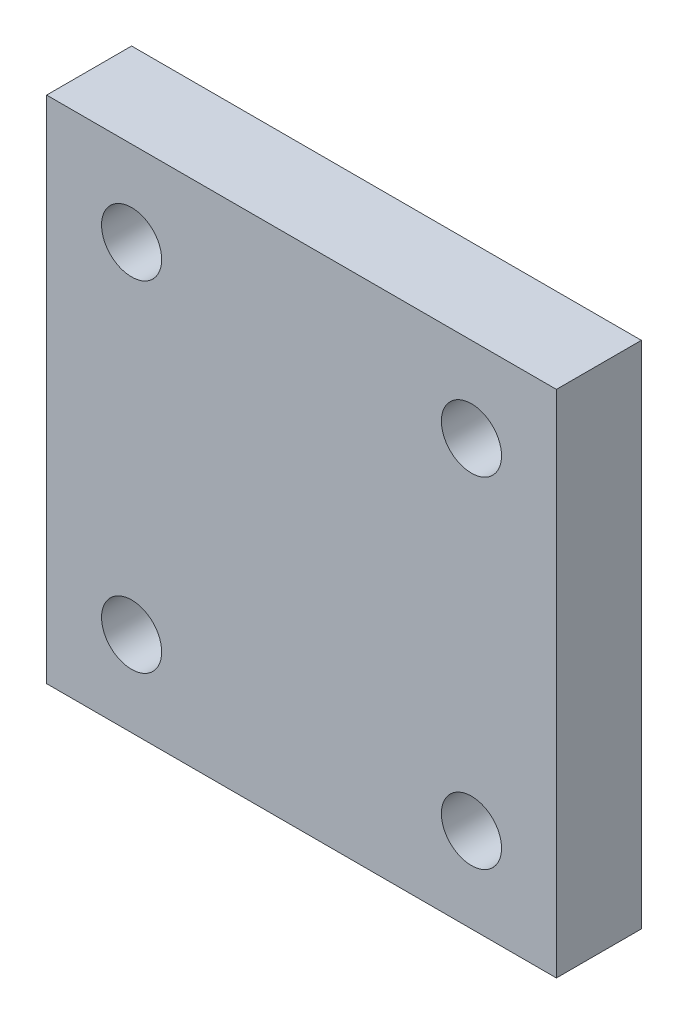
SolidWorks part; units mm, degrees
ref_plane "Front Plane" through (0, 0, 0) normal (0, 0, 1) x (1, 0, 0)
ref_plane "Top Plane" through (0, 0, 0) normal (0, 1, 0) x (1, 0, 0)
ref_plane "Right Plane" through (0, 0, 0) normal (1, 0, 0) x (0, 0, -1)
sketch "Sketch1" plane through (0, 0, 0) normal (0, 0, 1) x (1, 0, 0)
  line L1 (-19.05, 19.05) -> (19.05, 19.05)
  line L2 (-19.05, 19.05) -> (-19.05, -19.05)
  line L3 (-19.05, -19.05) -> (19.05, -19.05)
  line L4 (19.05, 19.05) -> (19.05, -19.05)
  line L5 (-19.05, 19.05) -> (19.05, -19.05) construction
  line L6 (-19.05, -19.05) -> (19.05, 19.05) construction
  line L7 (12.7, -12.7) -> (-12.7, -12.7) construction
  line L8 (12.7, -12.7) -> (12.7, 12.7) construction
  line L9 (12.7, 12.7) -> (-12.7, 12.7) construction
  line L10 (-12.7, -12.7) -> (-12.7, 12.7) construction
  line L11 (12.7, -12.7) -> (-12.7, 12.7) construction
  line L12 (12.7, 12.7) -> (-12.7, -12.7) construction
  circle A0 centre (-12.7, 12.7) radius 2.2479
  circle A1 centre (12.7, 12.7) radius 2.2479
  circle A2 centre (12.7, -12.7) radius 2.2479
  circle A3 centre (-12.7, -12.7) radius 2.2479
  point P0 (0, 0)
  point P6 (0, 0)
  dimension "D5" = 4.4958
  dimension "D1" = 38.1
  dimension "D2" = 38.1
  dimension "D3" = 6.35
  dimension "D4" = 6.35
extrude "Boss-Extrude1" add sketch "Sketch1" along normal blind 6.35
